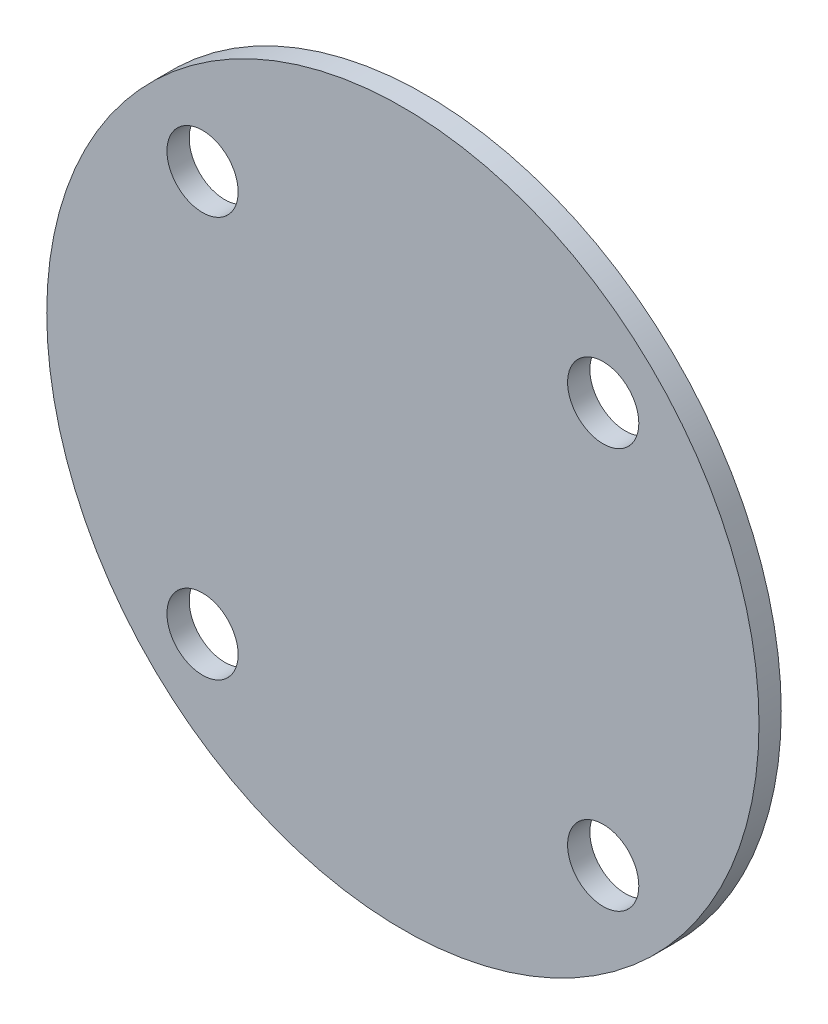
SolidWorks part; units mm, degrees
ref_plane "Front Plane" through (0, 0, 0) normal (0, 0, 1) x (1, 0, 0)
ref_plane "Top Plane" through (0, 0, 0) normal (0, 1, 0) x (1, 0, 0)
ref_plane "Right Plane" through (0, 0, 0) normal (1, 0, 0) x (0, 0, -1)
sketch "Sketch1" plane through (0, 0, 0) normal (0, 0, 1) x (1, 0, 0)
  circle A0 centre (0, 0) radius 16
extrude "Boss-Extrude1" add sketch "Sketch1" along normal blind 1
sketch "Sketch2" plane through (0, 0, 1) normal (0, 0, 1) x (1, 0, 0)
  circle A0 centre (0, 0) radius 2.5
  dimension "D1" = 5
extrude "Cut-Extrude1" [suppressed] cut sketch "Sketch2" against normal through all
sketch "Sketch3" [suppressed] plane through (0, 0, 3) normal (0, 0, 1) x (1, 0, 0)
  circle A0 centre (0, 0) radius 17.5
  dimension "D1" = 35
extrude "Boss-Extrude2" [suppressed] add sketch "Sketch3" along normal blind 10
sketch "Sketch4" [suppressed] plane through (0, 0, 3.7) normal (0, 0, 1) x (1, 0, 0)
  circle A0 centre (0, 0) radius 17.575
  dimension "D1" = 35.15
extrude "Boss-Extrude3" [suppressed] add sketch "Sketch4" along normal blind 7
sketch "Sketch5" [suppressed] plane through (0, 0, 0) normal (0, 0, -1) x (-1, 0, 0)
  circle A0 centre (0, 15) radius 1.6
  circle A1 centre (12.9904, 7.5) radius 1.6
  circle A2 centre (12.9904, -7.5) radius 1.6
  circle A3 centre (0, -15) radius 1.6
  circle A4 centre (-12.9904, -7.5) radius 1.6
  circle A5 centre (-12.9904, 7.5) radius 1.6
  point P9 (0, 0)
  dimension "D2" = 3.2
  dimension "D1" = 15
  dimension "D3" = 3
extrude "Cut-Extrude2" [suppressed] cut sketch "Sketch5" against normal through all
sketch "Sketch6" [suppressed] plane through (0, 0, 0) normal (0, 0, -1) x (-1, 0, 0)
  circle A0 centre (0, 0) radius 3
  circle A1 centre (0, 0) radius 20 construction
  circle A2 centre (0, 0) radius 20
  dimension "D1" = 6
extrude "Boss-Extrude4" [suppressed] add sketch "Sketch6" along normal up to surface (0.625 mm away)
sketch "Sketch11" [suppressed] plane through (0, 0, 4) normal (0, 0, 1) x (1, 0, 0)
  circle A8 centre (-10.0761, 0.6735) radius 1.6 construction
  circle A9 centre (0.6735, 10.0761) radius 1.6 construction
  circle A10 centre (10.0761, -0.6735) radius 1.6 construction
  circle A11 centre (-0.6735, -10.0761) radius 1.6 construction
  circle A12 centre (-10.0761, 0.6735) radius 1.6
  circle A13 centre (0.6735, 10.0761) radius 1.6
  circle A14 centre (10.0761, -0.6735) radius 1.6
  circle A15 centre (-0.6735, -10.0761) radius 1.6
extrude "Cut-Extrude3" [suppressed] cut sketch "Sketch11" against normal through all
sketch "Sketch12" plane through (0, 0, 0) normal (0, 0, 1) x (1, 0, 0)
  line L1 (-9, -9) -> (9, -9) construction
  line L2 (-9, -9) -> (-9, 9) construction
  line L3 (-9, 9) -> (9, 9) construction
  line L4 (9, -9) -> (9, 9) construction
  line L5 (-9, -9) -> (9, 9) construction
  line L6 (-9, 9) -> (9, -9) construction
  circle A0 centre (9, 9) radius 1.6
  circle A1 centre (9, -9) radius 1.6
  circle A2 centre (-9, -9) radius 1.6
  circle A3 centre (-9, 9) radius 1.6
  point P0 (0, 0)
  dimension "D1" = 3.2
  dimension "D2" = 18
extrude "Cut-Extrude4" cut sketch "Sketch12" along normal through all
equation "\"OD\"= 32mm"
equation "\"ID\"= 5"
equation "\"T\"= 0.5mm"
equation "\"D1\"= \"T\""
equation "\"D1@Sketch1\"=\"OD\""
equation "\"D1@Sketch2\"=\"ID\""
equation "\"D1@Boss-Extrude1\"=\"T\""
